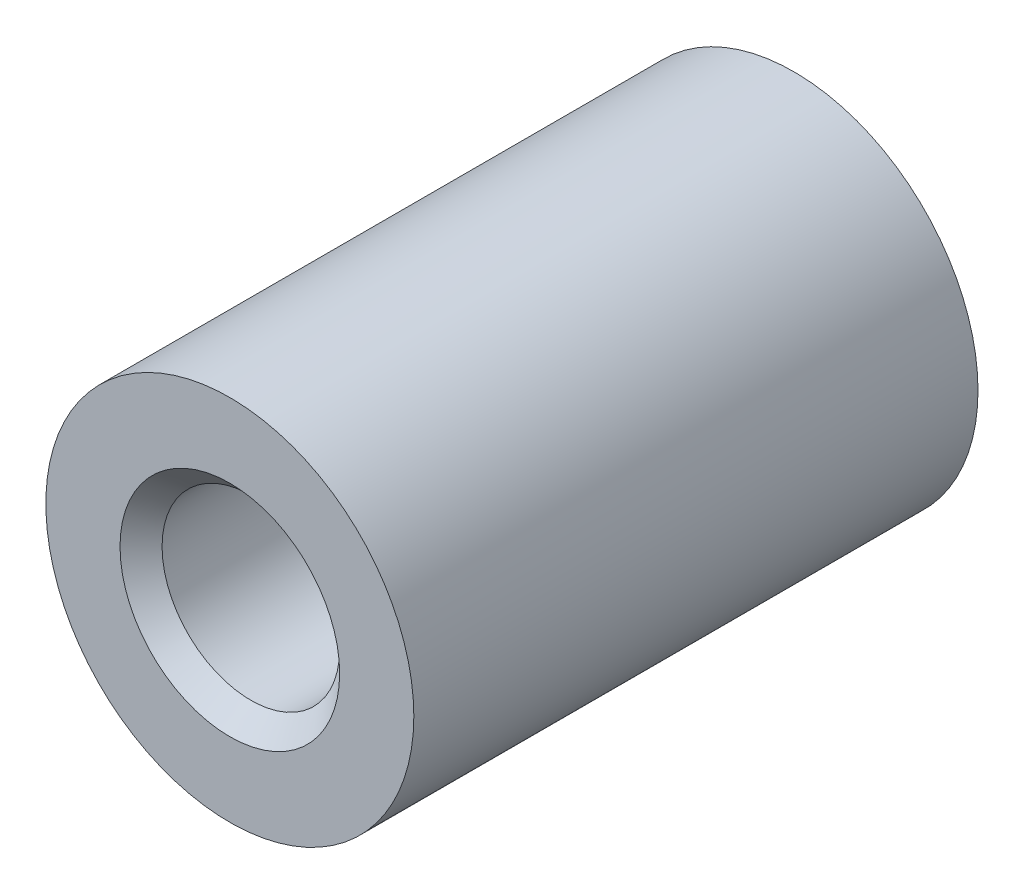
SolidWorks part; units mm, degrees
ref_plane "Front Plane" through (0, 0, 0) normal (0, 0, 1) x (1, 0, 0)
ref_plane "Top Plane" through (0, 0, 0) normal (0, 1, 0) x (1, 0, 0)
ref_plane "Right Plane" through (0, 0, 0) normal (1, 0, 0) x (0, 0, -1)
sketch "Sketch1" plane through (0, 0, 0) normal (0, 0, 1) x (1, 0, 0)
  circle A0 centre (0, 0) radius 6.04
  dimension "D1" = 12.08
extrude "Boss-Extrude1" add sketch "Sketch1" along normal blind 18.52
ref_plane "Plane1" through (0, 0, 18.52) normal (0, 0, 1) x (1, 0, 0)
sketch "Sketch2" plane through (0, 0, 18.52) normal (0, 0, 1) x (1, 0, 0)
  circle A0 centre (0, 0) radius 2.405
  dimension "D1" = 4.81
extrude "Cut-Extrude1" cut sketch "Sketch2" against normal blind 18.52
sketch "Sketch3" plane through (0, 0, 18.52) normal (0, 0, 1) x (1, 0, 0)
  circle A0 centre (0, 0) radius 2.915
  dimension "D1" = 5.83
extrude "Cut-Extrude2" cut sketch "Sketch3" against normal blind 18.52
chamfer "Chamfer1" distance 0.69 angle 45 1 edges at (2.915, 0, 18.52)
chamfer "Chamfer2" distance 0.69 angle 45 1 edges at (2.915, 0, 0)
